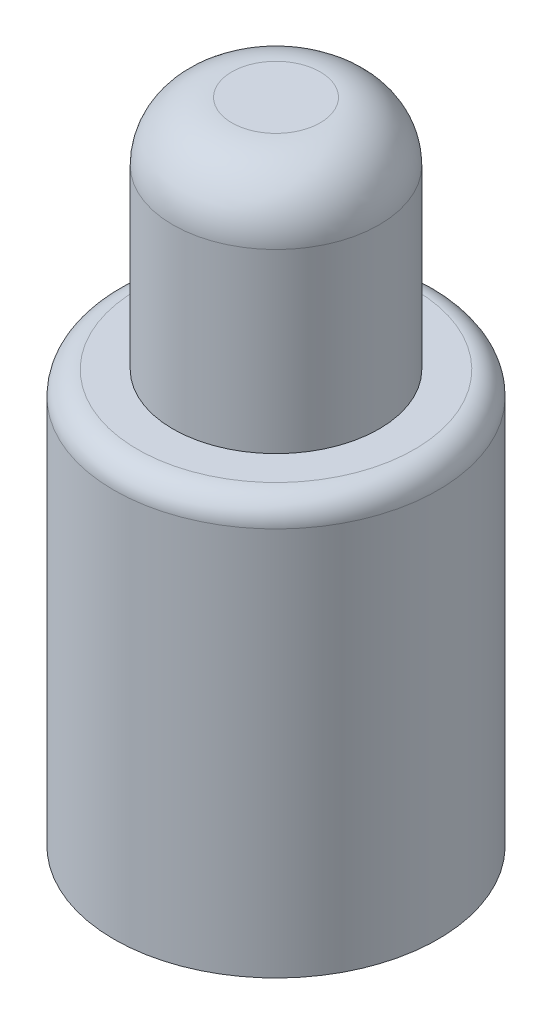
SolidWorks part; units mm, degrees
ref_plane "Front Plane" through (0, 0, 0) normal (0, 0, 1) x (1, 0, 0)
ref_plane "Top Plane" through (0, 0, 0) normal (0, 1, 0) x (1, 0, 0)
ref_plane "Right Plane" through (0, 0, 0) normal (1, 0, 0) x (0, 0, -1)
sketch "Sketch1" plane through (0, 0, 0) normal (0, 0, 1) x (1, 0, 0)
  line L0 (0, 0) -> (2.75, 0)
  line L1 (2.75, 0) -> (2.75, 7)
  line L2 (2.75, 7) -> (1.75, 7)
  line L3 (1.75, 7) -> (1.75, 11)
  line L4 (1.75, 11) -> (0, 11)
  line L5 (0, 11) -> (0, 0)
  line L6 (0, 0) -> (0, -3.2206) construction
  dimension "D1" = 3.5
  dimension "D2" = 5.5
  dimension "D3" = 4
  dimension "D4" = 7
revolve "Revolve1" add sketch "Sketch1" angle 360 about L6
fillet "Fillet1" radius 1 1 edges at (0, 11, 1.75)
fillet "Fillet2" radius 0.4 1 edges at (0, 7, 2.75)
